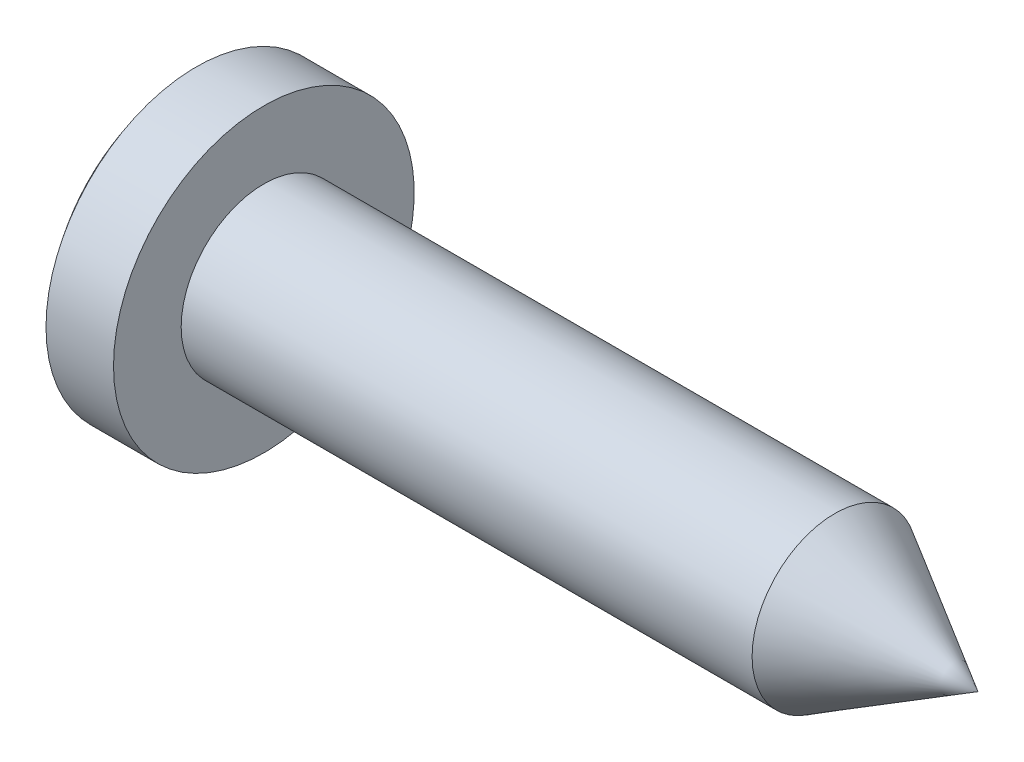
SolidWorks part; units mm, degrees
ref_plane "Front Plane" through (0, 0, 0) normal (0, 0, 1) x (1, 0, 0)
ref_plane "Top Plane" through (0, 0, 0) normal (0, 1, 0) x (1, 0, 0)
ref_plane "Right Plane" through (0, 0, 0) normal (1, 0, 0) x (0, 0, -1)
sketch "Sketch1" plane through (0, 0, 0) normal (0, 0, 1) x (1, 0, 0)
  line L0 (0, 0) -> (5.2282, 0) construction
  line L2 (0, 2) -> (-0.898, 2)
  line L3 (-1.6, 0) -> (-1.6, -0.7496) construction
  line L4 (-1.6, 0) -> (9.5, 0)
  line L5 (0, 1.1) -> (9.5, 1.1)
  line L6 (9.5, 1.1) -> (9.5, 0)
  line L7 (0, 1.1) -> (0, 2)
  arc A0 (-0.898, 2) -> (-1.6, 0) centre (1.6, 0) ccw
  dimension "rf" = 3.2
  dimension "Dk" = 4
  dimension "K" = 1.6
  dimension "d" = 2.2
  dimension "l" = 9.5
revolve "Revolve1" add sketch "Sketch1" angle 360 about L0
cosmetic thread "ThreadCosmetic" [suppressed] parameters "D1"=9.28, "D2"=1.63
chamfer "Chamfer1" distance 0.22 angle 60 1 edges at (9.5, 0, 1.1)
sketch "Sketch5" plane through (0, 0, 0) normal (0, 0, 1) x (1, 0, 0)
  line L0 (0.7155, 0.815) -> (0.2445, 0.815)
  line L1 (0.2445, 0.815) -> (0.08, 1.1)
  line L2 (0.7155, 0.815) -> (0.88, 1.1)
  line L3 (0.08, 1.1) -> (0.08, 1.35)
  line L4 (0.88, 1.1) -> (0.88, 1.35)
  line L5 (0.08, 1.35) -> (0.88, 1.35)
  line L6 (0.48, 0.815) -> (0.48, 0) construction
  line L7 (0, 0) -> (7.3035, 0) construction
  line L9 (9.1189, 1.1) -> (0, 1.1) construction
  line L12 (0, -1.1) -> (0, 1.1) construction
  dimension "D2" = 60
  dimension "D3" = 0.25
  dimension "advance" = 0.8
  dimension "minordia" = 1.63
  dimension "threadstart" = 0.48
revolve "ThreadSchematic" [suppressed] cut sketch "Sketch5" angle 360 about L7
pattern_linear "ThdSchPat" [suppressed] count 12 spacing 0.8 along (1, 0, 0)
sketch "Sketch2" plane through (0, 0, 0) normal (0, 0, 1) x (1, 0, 0)
  line L0 (0, 0) -> (5.7679, 0) construction
  line L1 (9.5, 0) -> (7.5947, 1.1)
  line L3 (9.5, 1.1) -> (9.5, 0) construction
  line L4 (7.5947, 1.1) -> (7.5947, 1.2)
  line L5 (7.5947, 1.2) -> (9.6, 1.2)
  line L6 (9.6, 1.2) -> (9.6, 0)
  line L7 (9.6, 0) -> (9.5, 0)
  point P9 (0, 1.1)
  dimension "D1" = 30
  dimension "D2" = 0.1
  dimension "D3" = 0.1
revolve "EndCone" cut sketch "Sketch2" angle 360 about L0
ref_plane "Plane4" through (-1.6, 0, 0) normal (1, 0, 0) x (0, 0, -1)
sketch "Sketch3" plane through (-1.6, 0, 0) normal (1, 0, 0) x (0, 0, -1)
  line L0 (0, 2.343) -> (0, -2.4842) construction
  line L1 (2.7661, 0) -> (-3.4558, 0) construction
  line L2 (-0.2375, 0.95) -> (0.2375, 0.95)
  line L3 (0.2375, 0.95) -> (0.1425, 0.57)
  line L4 (0, 0) -> (1.9578, 1.9578) construction
  line L5 (0.1425, 0.57) -> (0.299, 0.299)
  line L6 (0.1425, 0.57) -> (0, 0) construction
  line L7 (-0.1425, 0.57) -> (-0.299, 0.299)
  line L8 (-0.2375, 0.95) -> (-0.1425, 0.57)
  line L9 (0.95, 0.2375) -> (0.95, -0.2375)
  line L10 (0.95, -0.2375) -> (0.57, -0.1425)
  line L11 (0.57, -0.1425) -> (0.299, -0.299)
  line L12 (0.57, 0.1425) -> (0.299, 0.299)
  line L13 (0.95, 0.2375) -> (0.57, 0.1425)
  line L14 (0.2375, -0.95) -> (-0.2375, -0.95)
  line L15 (-0.2375, -0.95) -> (-0.1425, -0.57)
  line L16 (-0.1425, -0.57) -> (-0.299, -0.299)
  line L17 (0.1425, -0.57) -> (0.299, -0.299)
  line L18 (0.2375, -0.95) -> (0.1425, -0.57)
  line L19 (-0.95, -0.2375) -> (-0.95, 0.2375)
  line L20 (-0.95, 0.2375) -> (-0.57, 0.1425)
  line L21 (-0.57, 0.1425) -> (-0.299, 0.299)
  line L22 (-0.57, -0.1425) -> (-0.299, -0.299)
  line L23 (-0.95, -0.2375) -> (-0.57, -0.1425)
  point P14 (0, 0.95)
  point P23 (0.95, 0)
  point P30 (0, -0.95)
  point P37 (-0.95, 0)
  dimension "D1" = 45
  dimension "m" = 1.9
  dimension "D3" = 0.475
  dimension "D4" = 75
  dimension "D5" = 1.14
extrude "Cut-Extrude1" cut sketch "Sketch3" along normal blind 0.85 draft 6
sketch "Sketch4" plane through (-1.6, 0, 0) normal (1, 0, 0) x (0, 0, -1)
  line L0 (0, 2.1951) -> (0, -2.1951) construction
  line L1 (2.1996, 0) -> (-2.3835, 0) construction
  line L2 (-0.8397, -0.8397) -> (0.8397, 0.8397) construction
  line L3 (0.95, 0.2375) -> (-0.95, 0.2375)
  line L4 (0.95, 0.2375) -> (0.95, -0.2375)
  line L5 (0.95, -0.2375) -> (-0.95, -0.2375)
  line L6 (-0.95, 0.2375) -> (-0.95, -0.2375)
  line L7 (0.2375, 0.95) -> (-0.2375, 0.95)
  line L8 (0.2375, 0.95) -> (0.2375, -0.95)
  line L9 (0.2375, -0.95) -> (-0.2375, -0.95)
  line L10 (-0.2375, 0.95) -> (-0.2375, -0.95)
  line L11 (0.8397, 0.8397) -> (0.3859, 0.2375)
  line L12 (0.8397, 0.8397) -> (0.2375, 0.3859)
  line L13 (0.2375, 0.3859) -> (-0.2375, 0.3859) construction
  line L14 (0, 0) -> (-0.8397, 0.8397) construction
  line L15 (-0.8397, -0.8397) -> (-0.2375, -0.3859)
  line L16 (-0.8397, -0.8397) -> (-0.3859, -0.2375)
  line L17 (-0.2375, 0.3859) -> (-0.8397, 0.8397)
  line L18 (-0.8397, 0.8397) -> (-0.3859, 0.2375)
  line L19 (-0.3859, -0.2375) -> (-0.3859, 0.2375) construction
  line L20 (0.3859, -0.2375) -> (0.8397, -0.8397)
  line L21 (0.8397, -0.8397) -> (0.2375, -0.3859)
  circle A0 centre (0, 0) radius 1.1875 construction
  dimension "m" = 1.9
  dimension "D1" = 2.375
  dimension "D2" = 0.475
  dimension "D3" = 45
  dimension "D4" = 8
  dimension "D5" = 45
extrude "TypeZ" [suppressed] cut sketch "Sketch4" along normal blind 0.8
equation "\"D1@Chamfer1\" = \"d@Sketch1\"/10"
equation "\"D1@ThreadCosmetic\" = \"l@Sketch1\" - \"D1@Chamfer1\""
equation "\"minordia@Sketch5\" = \"D2@ThreadCosmetic\""
equation "\"D1@Plane4\" = \"K@Sketch1\""
equation "\"D5@Sketch3\" = \"m@Sketch3\" * 3 / 5"
equation "\"D3@Sketch3\" = \"m@Sketch3\" / 4"
equation "\"D2@Sketch4\" =  \"m@Sketch4\" / 4"
equation "\"D1@TypeZ\" = \"K@Sketch1\" / 2"
equation "\"D1@Sketch4\" = \"m@Sketch4\" * 5 / 4"
equation "\"m@Sketch4\" = \"m@Sketch3\""
equation "\"threadstart@Sketch5\" = \"advance@Sketch5\"*0.6"
equation "\"D1@ThdSchPat\" = int((\"l@Sketch1\"/\"advance@Sketch5\") + 0.999)"
equation "\"D3@ThdSchPat\" = \"advance@Sketch5\""
